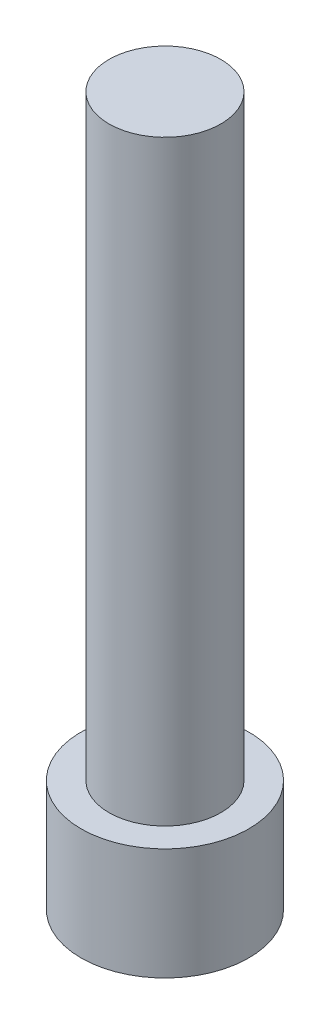
SolidWorks part; units mm, degrees
ref_plane "前视基准面" through (0, 0, 0) normal (0, 0, 1) x (1, 0, 0)
ref_plane "上视基准面" through (0, 0, 0) normal (0, 1, 0) x (1, 0, 0)
ref_plane "右视基准面" through (0, 0, 0) normal (1, 0, 0) x (0, 0, -1)
other "Configuration Table"
sketch "草图1" plane through (0, 0, 0) normal (0, 1, 0) x (1, 0, 0)
  circle A0 centre (0, 0) radius 2.25
  dimension "D1" = 4.5
extrude "凸台-拉伸1" add sketch "草图1" along normal blind 3
sketch "草图2" plane through (0, 3, 0) normal (0, 1, 0) x (1, 0, 0)
  circle A0 centre (0, 0) radius 1.5
  dimension "D1" = 3
extrude "凸台-拉伸2" add sketch "草图2" along normal blind 16
cosmetic thread "装饰螺纹线1" parameters "D2"=2
sketch "草图3" plane through (0, 0, 0) normal (0, -1, 0) x (1, 0, 0)
  line L1 (1.0917, -0.9442) -> (1.3636, 0.4733)
  line L2 (1.3636, 0.4733) -> (0.2719, 1.4175)
  line L3 (0.2719, 1.4175) -> (-1.0917, 0.9442)
  line L4 (-1.0917, 0.9442) -> (-1.3636, -0.4733)
  line L5 (-1.3636, -0.4733) -> (-0.2719, -1.4175)
  line L6 (-0.2719, -1.4175) -> (1.0917, -0.9442)
  circle A0 centre (0, 0) radius 1.25 construction
  dimension "D1" = 2.5
extrude "切除-拉伸1" cut sketch "草图3" against normal blind 1.5
